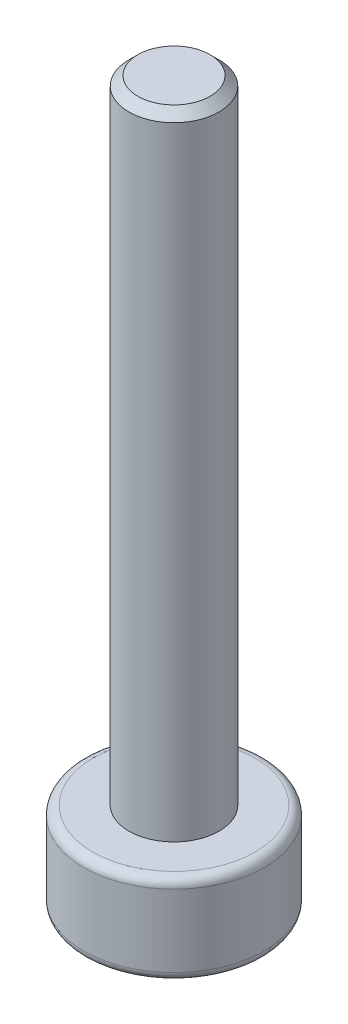
SolidWorks part; units mm, degrees
material "AISI 304"
ref_plane "前视基准面" through (0, 0, 0) normal (0, 0, 1) x (1, 0, 0)
ref_plane "上视基准面" through (0, 0, 0) normal (0, 1, 0) x (1, 0, 0)
ref_plane "右视基准面" through (0, 0, 0) normal (1, 0, 0) x (0, 0, -1)
sketch "草图2" plane through (0, 0, 0) normal (0, 1, 0) x (1, 0, 0)
  circle A0 centre (0, 0) radius 2
  dimension "D1" = 4
extrude "凸台-拉伸1" add sketch "草图2" along normal blind 2
sketch "草图3" plane through (0, 2, 0) normal (0, 1, 0) x (1, 0, 0)
  circle A0 centre (0, 0) radius 1
  dimension "D1" = 2
extrude "凸台-拉伸2" add sketch "草图3" along normal blind 14
fillet "圆角1" radius 0.2 2 edges at (0, 2, 2) (0, 0, 2)
sketch "草图4" plane through (0, 0, 0) normal (0, -1, 0) x (1, 0, 0)
  circle A0 centre (0, 0) radius 0.765
  dimension "D1" = 1.53
extrude "切除-拉伸1" cut sketch "草图4" against normal blind 1.52
chamfer "倒角1" distance 0.1 angle 45 1 edges at (0, 0, -0.765)
chamfer "倒角2" distance 0.2 angle 45 1 edges at (0, 16, 1)
